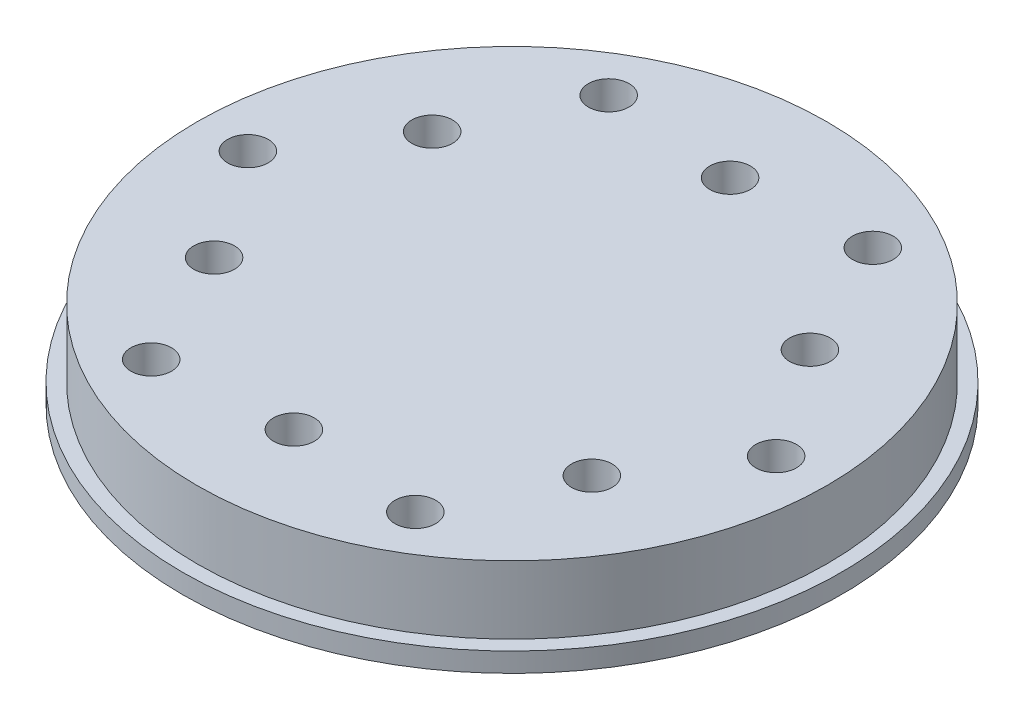
SolidWorks part; units mm, degrees
ref_plane "Front Plane" through (0, 0, 0) normal (0, 0, 1) x (1, 0, 0)
ref_plane "Top Plane" through (0, 0, 0) normal (0, 1, 0) x (1, 0, 0)
ref_plane "Right Plane" through (0, 0, 0) normal (1, 0, 0) x (0, 0, -1)
sketch "Sketch2" plane through (0, 0, 0) normal (0, 1, 0) x (1, 0, 0)
  circle A0 centre (0, 0) radius 27.25 construction
  circle A1 centre (0, 0) radius 32.5
  circle A2 centre (0, 0) radius 6.5
  circle A3 centre (27.25, 0) radius 1.5
  circle A4 centre (13.625, -23.5992) radius 1.5
  circle A5 centre (-13.625, -23.5992) radius 1.5
  circle A6 centre (-27.25, 0) radius 1.5
  circle A7 centre (-13.625, 23.5992) radius 1.5
  circle A8 centre (13.625, 23.5992) radius 1.5
  point P22 (0, 0)
  dimension "D1" = 54.5
  dimension "D4" = 3
  dimension "D3" = 13
  dimension "D2" = 65
  dimension "D5" = 6
extrude "Boss-Extrude1" add sketch "Sketch2" along normal blind 10
hole_wizard "M5x0.8 Tapped Hole1" positions "Sketch6" profile "Sketch7" tap size "M5x0.8" standard "ANSI Metric" end condition through all
sketch "Sketch6" plane through (0, 10, 0) normal (0, 1, 0) x (1, 0, 0)
  point P0 (-13.625, 23.5992)
  point P8 (13.625, 23.5992)
  point P9 (27.25, 0)
  point P10 (13.625, -23.5992)
  point P11 (-13.625, -23.5992)
  point P12 (-27.25, 0)
  dimension "D1" = 6
sketch "Sketch7" plane through (-13.625, 10, -23.5992) normal (1, 0, 0) x (0, 0, 1)
  line L0 (0, 0) -> (0, 10)
  line L1 (0, 10) -> (2.1, 10)
  line L2 (2.1, 10) -> (2.1, 0)
  line L5 (2.1, 0) -> (0, 0)
  line L11 (0, -6.35) -> (0, 107.95) construction
  dimension "Thru Tap Drill Dia." = 4.2
  dimension "Thru Tap Drill Depth" = 10
cosmetic thread "Hole Thread1"
cosmetic thread "Hole Thread2"
cosmetic thread "Hole Thread3"
cosmetic thread "Hole Thread4"
cosmetic thread "Hole Thread5"
cosmetic thread "Hole Thread6"
sketch "Sketch8" plane through (0, 10, 0) normal (0, 1, 0) x (1, 0, 0)
  circle A0 centre (0, 0) radius 6.5 construction
  circle A1 centre (0, 0) radius 6.5
extrude "Boss-Extrude2" add sketch "Sketch8" against normal blind 6.5
sketch "Sketch9" plane through (0, 0, 0) normal (0, -1, 0) x (1, 0, 0)
  circle A0 centre (0, 0) radius 32.5 construction
  circle A1 centre (0, 0) radius 32.5
  circle A2 centre (0, 0) radius 17.5
  dimension "D1" = 35
extrude "Cut-Extrude1" cut sketch "Sketch9" against normal blind 1
sketch "Sketch10" plane through (0, 0, 0) normal (1, 0, 0) x (0, 0, -1)
  line L0 (0, 0) -> (0, 10) construction
  line L1 (-32.5, 1) -> (-34, 1)
  line L2 (-32.5, 1) -> (-32.5, 3)
  line L3 (-32.5, 3) -> (-34, 3)
  line L4 (-34, 1) -> (-34, 3)
  line L5 (2.1, 10) -> (-2.1, 10) construction
  dimension "D1" = 2
  dimension "D2" = 1.5
revolve "Revolve1" add sketch "Sketch10" angle 360 about L0
hole_wizard "M5x0.8 Tapped Hole2" positions "Sketch11" profile "Sketch12" tap size "M5x0.8" standard "ANSI Metric" end condition through all
sketch "Sketch11" plane through (0, 10, 0) normal (0, 1, 0) x (1, 0, 0)
  line L0 (0, 0) -> (0, 32.5) construction
  circle A0 centre (0, 0) radius 32.5 construction
  point P0 (0, 22.5)
  point P19 (19.4856, 11.25)
  point P21 (19.4856, -11.25)
  point P23 (0, -22.5)
  point P25 (-19.4856, -11.25)
  point P27 (-19.4856, 11.25)
  point P30 (0, 0)
  point P31 (0, 0)
  point P32 (0, 0)
  point P33 (0, 0)
  point P34 (0, 0)
  point P35 (0, 0)
  dimension "D1" = 10
  dimension "D2" = 10
  dimension "D3" = 6
sketch "Sketch12" plane through (0, 10, -22.5) normal (1, 0, 0) x (0, 0, 1)
  line L0 (0, 0) -> (0, 10)
  line L1 (0, 10) -> (2.1, 10)
  line L2 (2.1, 10) -> (2.1, 0)
  line L5 (2.1, 0) -> (0, 0)
  line L11 (0, -6.35) -> (0, 107.95) construction
  dimension "Thru Tap Drill Dia." = 4.2
  dimension "Thru Tap Drill Depth" = 10
cosmetic thread "Hole Thread8"
cosmetic thread "Hole Thread10"
cosmetic thread "Hole Thread12"
cosmetic thread "Hole Thread14"
cosmetic thread "Hole Thread16"
cosmetic thread "Hole Thread18"
